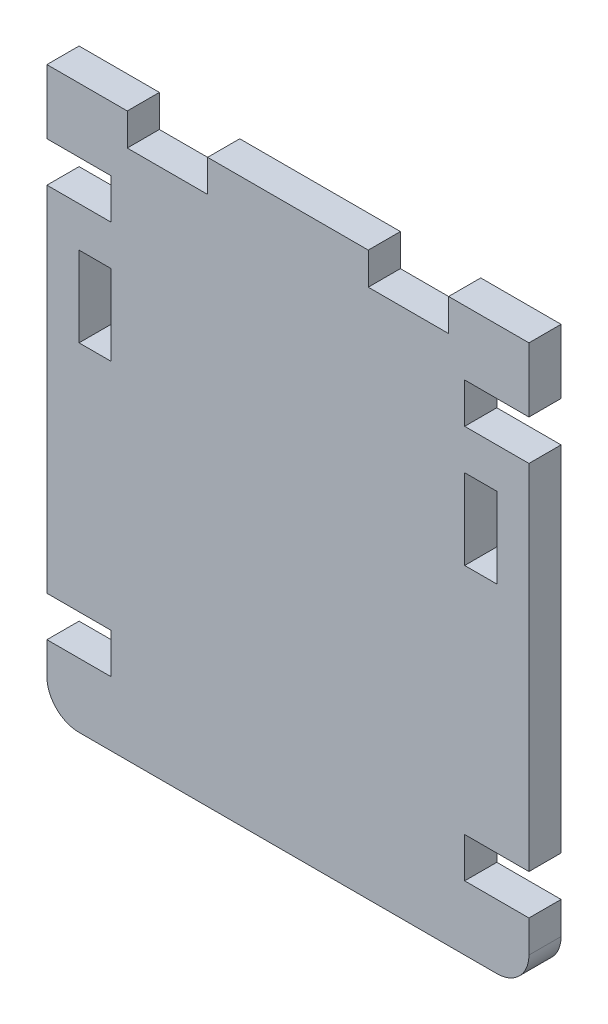
SolidWorks part; units mm, degrees
ref_plane "Front Plane" through (0, 0, 0) normal (0, 0, 1) x (1, 0, 0)
ref_plane "Top Plane" through (0, 0, 0) normal (0, 1, 0) x (1, 0, 0)
ref_plane "Right Plane" through (0, 0, 0) normal (1, 0, 0) x (0, 0, -1)
sketch "Sketch1" plane through (0, 0, 0) normal (0, 0, 1) x (1, 0, 0)
  line L0 (-30, -27) -> (-22, -27)
  line L1 (-30, 35) -> (-20, 35)
  line L2 (-30, -31) -> (-30, -27)
  line L3 (-26, -35) -> (26, -35)
  line L4 (30, -31) -> (30, -27)
  line L5 (-22, -27) -> (-22, -22)
  line L6 (-22, -22) -> (-30, -22)
  line L7 (30, 27) -> (30, 35)
  line L8 (-30, 27) -> (-22, 27)
  line L9 (-22, 27) -> (-22, 22)
  line L10 (-22, 22) -> (-30, 22)
  line L11 (-30, 22) -> (-30, -22)
  line L12 (-20, 35) -> (-20, 31)
  line L13 (22, -22) -> (30, -22)
  line L14 (22, -27) -> (22, -22)
  line L15 (30, -27) -> (22, -27)
  line L16 (22, 22) -> (30, 22)
  line L17 (22, 27) -> (22, 22)
  line L18 (30, 27) -> (22, 27)
  line L19 (30, 22) -> (30, -22)
  line L20 (-30, 27) -> (-30, 35)
  line L21 (-20, 31) -> (-10, 31)
  line L22 (-10, 31) -> (-10, 35)
  line L23 (30, 35) -> (20, 35)
  line L24 (20, 35) -> (20, 31)
  line L25 (20, 31) -> (10, 31)
  line L26 (10, 31) -> (10, 35)
  line L27 (10, 35) -> (-10, 35)
  line L29 (-26, 17) -> (-22, 17)
  line L30 (-26, 17) -> (-26, 7)
  line L31 (-26, 7) -> (-22, 7)
  line L32 (-22, 17) -> (-22, 7)
  line L33 (22, 17) -> (26, 17)
  line L34 (22, 17) -> (22, 7)
  line L35 (22, 7) -> (26, 7)
  line L36 (26, 17) -> (26, 7)
  arc A0 (30, -31) -> (26, -35) centre (26, -31) cw
  arc A1 (-26, -35) -> (-30, -31) centre (-26, -31) cw
  point P39 (30, -35)
  dimension "D22" = 4
  dimension "D2" = 35
  dimension "D3" = 30
  dimension "D4" = 30
  dimension "D5" = 8
  dimension "D6" = 5
  dimension "D7" = 8
  dimension "D8" = 8
  dimension "D9" = 10
  dimension "D10" = 8
  dimension "D11" = 8
  dimension "D12" = 4
  dimension "D13" = 10
  dimension "D14" = 35
  dimension "D15" = 8
  dimension "D16" = 5
  dimension "D17" = 4
  dimension "D18" = 10
  dimension "D19" = 4
  dimension "D20" = 4
  dimension "D21" = 5
extrude "Boss-Extrude2" add sketch "Sketch1" along normal blind 4
